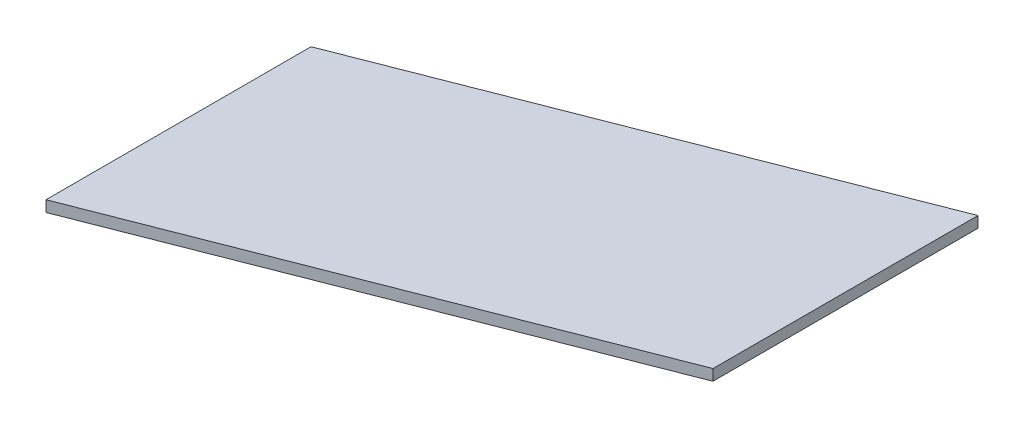
SolidWorks part; units mm, degrees
material "Ti-3Al-8V-6Cr-4Mo-4Zr (SS)"
ref_plane "Front Plane" through (0, 0, 0) normal (0, 0, 1) x (1, 0, 0)
ref_plane "Top Plane" through (0, 0, 0) normal (0, 1, 0) x (1, 0, 0)
ref_plane "Right Plane" through (0, 0, 0) normal (1, 0, 0) x (0, 0, -1)
sketch "Sketch1" plane through (0, 0, 0) normal (0, 1, 0) x (1, 0, 0)
  line L0 (0, 0) -> (0, 76.2)
  line L1 (0, 0) -> (137.922, 53.848)
  line L2 (0, 76.2) -> (137.922, 130.048)
  line L3 (137.922, 53.848) -> (137.922, 130.048)
  dimension "D1" = 76.2
  dimension "D2" = 137.922
  dimension "D3" = 53.848
extrude "Boss-Extrude1" add sketch "Sketch1" along normal blind 3.175
